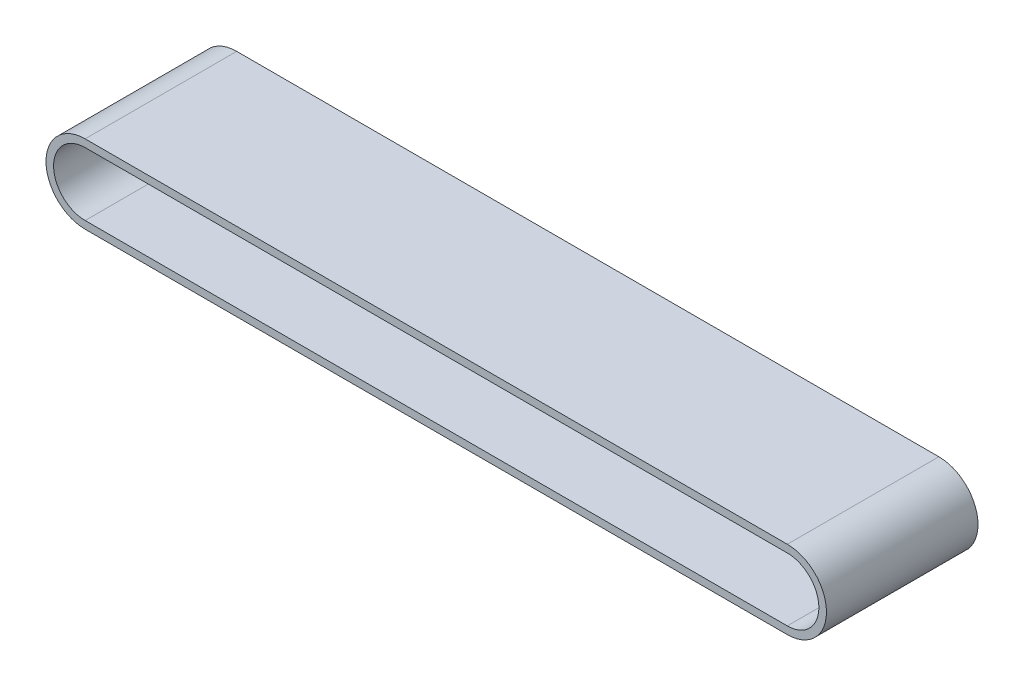
SolidWorks part; units mm, degrees
material "Caucho"
ref_plane "Alzado" through (0, 0, 0) normal (0, 0, 1) x (1, 0, 0)
ref_plane "Planta" through (0, 0, 0) normal (0, 1, 0) x (1, 0, 0)
ref_plane "Vista lateral" through (0, 0, 0) normal (1, 0, 0) x (0, 0, -1)
sketch "Croquis2" plane through (0, 0, 0) normal (0, 0, 1) x (1, 0, 0)
  line L0 (-29.712, 12.5) -> (248.288, 12.5) construction
  line L1 (-29.712, 25) -> (248.288, 25)
  line L2 (-29.712, 0) -> (248.288, 0)
  line L3 (-29.712, 28) -> (248.288, 28)
  line L4 (-29.712, -3) -> (248.288, -3)
  arc A0 (-29.712, 25) -> (-29.712, 0) centre (-29.712, 12.5) ccw
  arc A1 (248.288, 0) -> (248.288, 25) centre (248.288, 12.5) ccw
  arc A2 (248.288, -3) -> (248.288, 28) centre (248.288, 12.5) ccw
  arc A3 (-29.712, 28) -> (-29.712, -3) centre (-29.712, 12.5) ccw
  point P3 (109.288, 12.5)
  dimension "D1" = 12.5
  dimension "D2" = 278
  dimension "D3" = 3
extrude "Saliente-Extruir2" add sketch "Croquis2" along normal blind 60
